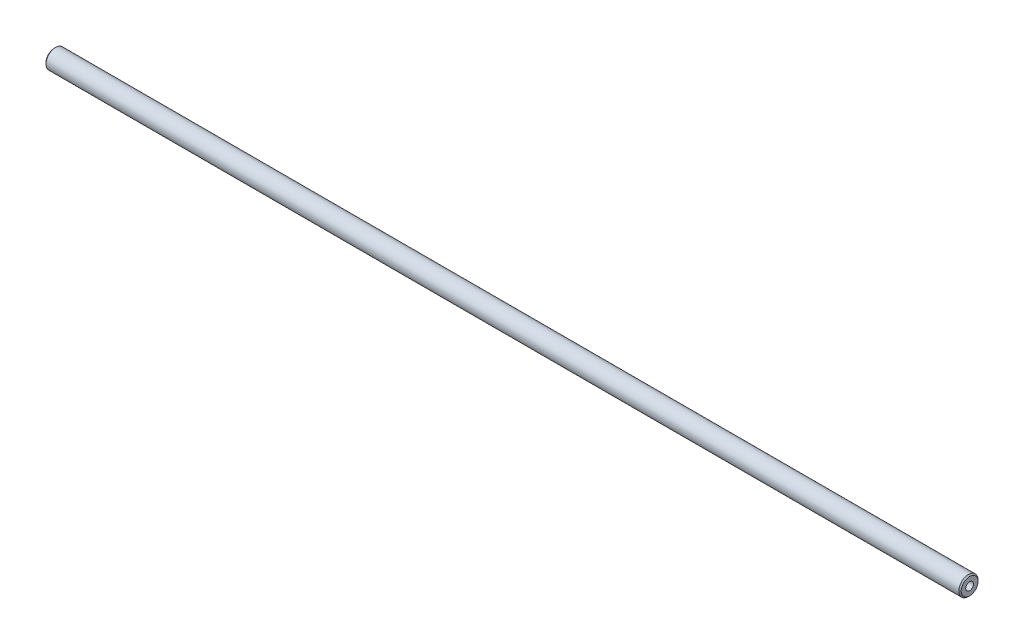
SolidWorks part; units mm, degrees
ref_plane "Front" through (0, 0, 0) normal (0, 0, 1) x (1, 0, 0)
ref_plane "Top" through (0, 0, 0) normal (0, 1, 0) x (1, 0, 0)
ref_plane "Right" through (0, 0, 0) normal (1, 0, 0) x (0, 0, -1)
sketch "Sketch1" plane through (0, 0, 0) normal (0, 0, 1) x (1, 0, 0)
  line L0 (-175.8, 1.621) -> (-174.826, 0)
  line L1 (-174.826, 0) -> (174.826, 0)
  line L2 (174.826, 0) -> (175.8, 1.621)
  line L3 (175.8, 1.621) -> (190.8, 1.621)
  line L4 (190.8, 1.621) -> (190.8, 3.5)
  line L5 (190.8, 3.5) -> (190.3, 4)
  line L6 (190.3, 4) -> (-190.3, 4)
  line L7 (-190.3, 4) -> (-190.8, 3.5)
  line L8 (-190.8, 3.5) -> (-190.8, 1.621)
  line L9 (-190.8, 1.621) -> (-175.8, 1.621)
  line L10 (-190.96, 0) -> (190.96, 0) construction
  line L11 (0, 0) -> (0, 33.7968) construction
  dimension "D1" = 3.242
  dimension "D2" = 15
  dimension "D3" = 59
  dimension "D4" = 45
  dimension "D5" = 0.5
  dimension "D6" = 381.6
  dimension "D7" = 8
revolve "Revolve1" add sketch "Sketch1" angle 360 about L10
